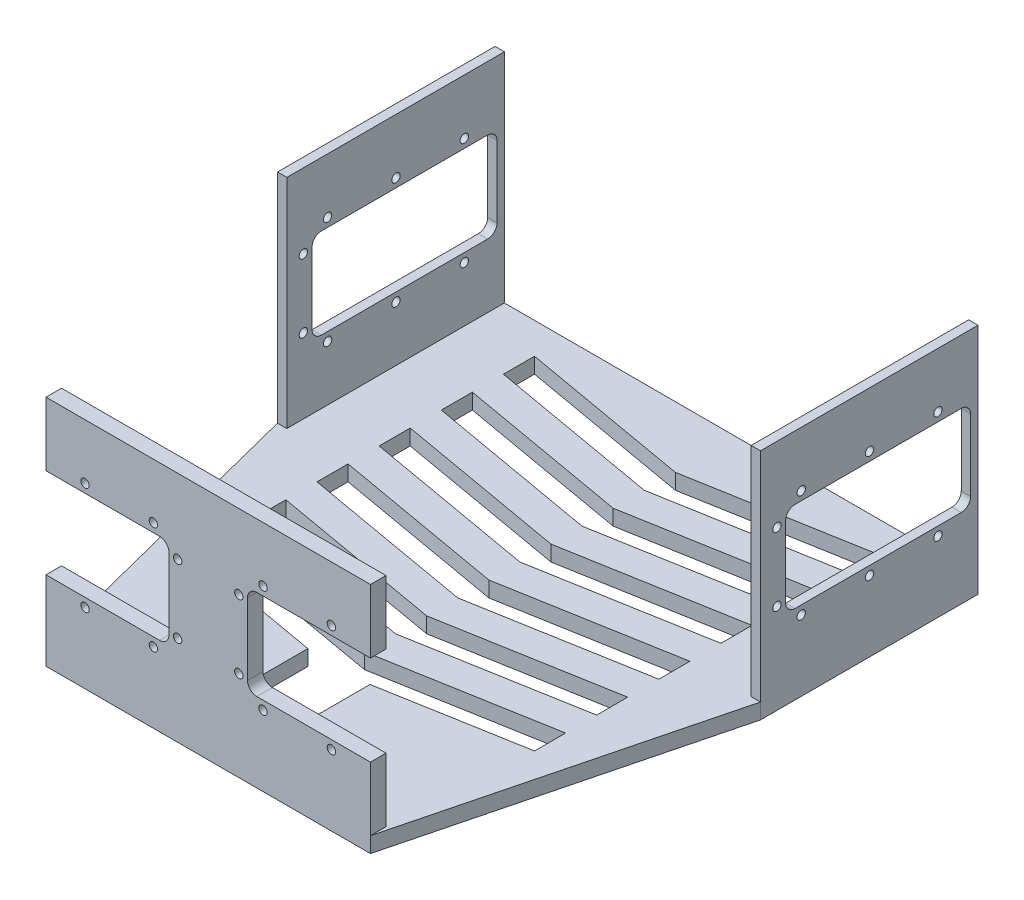
SolidWorks part; units mm, degrees
material "Aluminium 1050"
ref_plane "Front Plane" through (0, 0, 0) normal (0, 0, 1) x (1, 0, 0)
ref_plane "Top Plane" through (0, 0, 0) normal (0, 1, 0) x (1, 0, 0)
ref_plane "Right Plane" through (0, 0, 0) normal (1, 0, 0) x (0, 0, -1)
sketch "Sketch1" plane through (0, 0, 0) normal (0, 1, 0) x (1, 0, 0)
  line L0 (0, 0) -> (104.4, 0)
  line L4 (52.2, 0) -> (52.2, 170) construction
  line L5 (129.9, 100) -> (129.9, 170)
  line L6 (-25.5, 100) -> (-25.5, 170)
  line L7 (-25.5, 170) -> (129.9, 170)
  line L8 (-25.5, 100) -> (129.9, 100) construction
  line L9 (-25.5, 100) -> (0, 0)
  line L10 (104.4, 0) -> (129.9, 100)
  line L12 (-25.5, 0) -> (-25.5, 170) construction
  line L13 (129.9, 0) -> (129.9, 170) construction
  dimension "D1" = 104.4
  dimension "D2" = 170
  dimension "D3" = 77.7
  dimension "D4" = 77.7
  dimension "D5" = 70
extrude "Boss-Extrude1" add sketch "Sketch1" along normal blind 3
sketch "Sketch4" plane through (-25.5, 0, 0) normal (-1, 0, 0) x (0, 0, 1)
  line L0 (-170, 3) -> (-170, 73)
  line L1 (-170, 73) -> (-100, 73)
  line L2 (-100, 73) -> (-100, 3)
  line L3 (-170, 3) -> (-100, 3) construction
  line L4 (-100, 3) -> (-170, 3)
  dimension "D1" = 70
  dimension "D2" = 70
extrude "Boss-Extrude3" add sketch "Sketch4" against normal blind 3
sketch "Sketch5" plane through (129.9, 0, 0) normal (1, 0, 0) x (0, 0, -1)
  line L0 (170, 3) -> (170, 73)
  line L1 (170, 73) -> (100, 73)
  line L2 (100, 73) -> (100, 3)
  line L3 (100, 3) -> (170, 3)
extrude "Boss-Extrude4" add sketch "Sketch5" against normal blind 3
sketch "Sketch7" plane through (0, 0, 0) normal (0, 0, 1) x (1, 0, 0)
  line L7 (0, 3) -> (104.4, 3)
  line L11 (0, 3) -> (0, 73)
  line L15 (104.4, 3) -> (104.4, 73)
  line L29 (0, 0) -> (104.4, 0)
  line L30 (104.4, 0) -> (104.4, 3)
  line L31 (0, 73) -> (104.4, 73)
  point P0 (52.2, -22.1263)
  point P1 (52.2, 47.538)
  point P4 (109.5, -22.1263)
  point P5 (109.5, 47.538)
  point P6 (-5.1, -22.1263)
  point P8 (-5.1, 47.538)
  dimension "D1" = 70
extrude "Boss-Extrude5" add sketch "Sketch7" against normal blind 5
sketch "Sketch8" plane through (-22.5, 0, 0) normal (1, 0, 0) x (0, 0, -1)
  line L0 (111.05, 15.5) -> (164.55, 15.5) construction
  line L1 (167.55, 18.5) -> (167.55, 41.5) construction
  line L2 (164.55, 44.5) -> (111.05, 44.5) construction
  line L3 (108.05, 41.5) -> (108.05, 18.5) construction
  line L4 (135.05, -30.973) -> (135.05, 91.2848) construction
  line L5 (100, 38) -> (170, 38) construction
  line L6 (100, 3) -> (100, 73) construction
  line L7 (170, 73) -> (170, 0) construction
  circle A0 centre (157.05, 47.3) radius 1.35 construction
  circle A1 centre (135.05, 47.3) radius 1.35 construction
  circle A2 centre (113.05, 47.3) radius 1.35 construction
  circle A3 centre (105.25, 41) radius 1.35 construction
  circle A4 centre (105.25, 19) radius 1.35 construction
  circle A5 centre (113.05, 12.7) radius 1.35 construction
  circle A6 centre (157.05, 12.7) radius 1.35 construction
  circle A7 centre (135.05, 12.7) radius 1.35 construction
  arc A8 (164.55, 15.5) -> (167.55, 18.5) centre (164.55, 18.5) ccw construction
  arc A9 (167.55, 41.5) -> (164.55, 44.5) centre (164.55, 41.5) ccw construction
  arc A10 (111.05, 44.5) -> (108.05, 41.5) centre (111.05, 41.5) ccw construction
  arc A11 (111.05, 15.5) -> (108.05, 18.5) centre (111.05, 18.5) cw construction
  dimension "D1" = 2.7
  dimension "D2" = 2.7
  dimension "D3" = 2.7
  dimension "D4" = 2.7
  dimension "D5" = 2.7
  dimension "D6" = 2.7
  dimension "D7" = 2.7
  dimension "D8" = 2.7
sketch "Sketch22" plane through (0, 0, 0) normal (0, -1, 0) x (1, 0, 0)
  line L0 (129.9, -170) -> (-25.5, -170)
  line L1 (-25.5, -170) -> (-25.5, -100)
  line L2 (-25.5, -100) -> (0, 0)
  line L3 (0, 0) -> (104.4, 0)
  line L4 (104.4, 0) -> (129.9, -100)
  line L5 (129.9, -100) -> (129.9, -170)
extrude "Boss-Extrude13" add sketch "Sketch22" along normal blind 2
sketch "Sketch26" plane through (-25.5, 0, 0) normal (-1, 0, 0) x (0, 0, 1)
  line L0 (-170, 38) -> (-100, 38)
  line L1 (-170, 23.5) -> (-100, 23.5)
  line L2 (-170, 52.5) -> (-100, 52.5)
  circle A0 centre (-157.1137, 55.3) radius 1.35
  circle A1 centre (-135.1137, 55.3) radius 1.35
  circle A2 centre (-113.1137, 55.3) radius 1.35
  circle A3 centre (-105.3137, 49) radius 1.35
  circle A4 centre (-105.3137, 27) radius 1.35
  circle A5 centre (-113.1137, 20.7) radius 1.35
  circle A6 centre (-157.1137, 20.7) radius 1.35
  circle A7 centre (-135.1137, 20.7) radius 1.35
  dimension "D1" = 2.7
  dimension "D2" = 2.7
  dimension "D3" = 2.7
  dimension "D4" = 2.7
  dimension "D5" = 2.7
  dimension "D6" = 2.7
  dimension "D7" = 2.7
  dimension "D8" = 2.7
  dimension "D9" = 14.5
  dimension "D10" = 14.5
extrude "Cut-Extrude1" cut sketch "Sketch26" against normal through all both and the other way through all contours A6 | A5 | A4 | A3 | A2 | A1 | A0 | A7
sketch "Sketch28" plane through (-22.5, 0, 0) normal (1, 0, 0) x (0, 0, -1)
  line L2 (167.6137, 49.5) -> (167.6137, 26.5)
  line L3 (164.6137, 23.5) -> (111.1137, 23.5)
  line L4 (108.1137, 26.5) -> (108.1137, 49.5)
  line L5 (111.1137, 52.5) -> (164.6137, 52.5)
  arc A0 (167.6137, 26.5) -> (164.6137, 23.5) centre (164.6137, 26.5) cw
  arc A1 (111.1137, 23.5) -> (108.1137, 26.5) centre (111.1137, 26.5) cw
  arc A2 (108.1137, 49.5) -> (111.1137, 52.5) centre (111.1137, 49.5) cw
  arc A3 (111.1137, 52.5) -> (108.1137, 49.5) centre (111.1137, 49.5) ccw construction
  arc A4 (164.6137, 52.5) -> (167.6137, 49.5) centre (164.6137, 49.5) cw
extrude "Cut-Extrude3" cut sketch "Sketch28" against normal through all both and the other way through all
sketch "Sketch29" plane through (0, 0, -5) normal (0, 0, -1) x (-1, 0, 0)
  line L0 (-52.2, 3) -> (-52.2, 73)
  line L1 (-104.4, 3) -> (0, 3) construction
  line L2 (0, 73) -> (-104.4, 73) construction
  line L3 (5.1, 38) -> (-109.5, 38)
  line L6 (5.1, 3) -> (5.1, 73)
  line L7 (-109.5, 3) -> (-109.5, 73)
  dimension "D1" = 57.3
  dimension "D2" = 57.3
sketch "Sketch31" plane through (0, 0, -5) normal (0, 0, -1) x (-1, 0, 0)
  line L0 (-36.5639, 52.5) -> (0, 52.5)
  line L1 (-36.5639, 52.5) -> (16.9361, 52.5) construction
  line L2 (0, 3) -> (0, 73) construction
  line L3 (0, 52.5) -> (0, 23.5)
  line L4 (16.9361, 23.5) -> (-36.5639, 23.5) construction
  line L5 (0, 23.5) -> (-36.5639, 23.5)
  line L6 (-39.5639, 26.5) -> (-39.5639, 49.5)
  line L7 (-52.2, 3) -> (-52.2, 73)
  line L8 (-64.8361, 26.5) -> (-64.8361, 49.5)
  line L9 (-104.4, 23.5) -> (-67.8361, 23.5)
  line L10 (-104.4, 52.5) -> (-104.4, 23.5)
  line L11 (-67.8361, 52.5) -> (-104.4, 52.5)
  arc A0 (-36.5639, 52.5) -> (-39.5639, 49.5) centre (-36.5639, 49.5) ccw construction
  arc A1 (-36.5639, 23.5) -> (-39.5639, 26.5) centre (-36.5639, 26.5) cw
  arc A2 (-36.5639, 52.5) -> (-39.5639, 49.5) centre (-36.5639, 49.5) ccw
  circle A3 centre (-12.5639, 55.3) radius 1.35
  circle A4 centre (-34.5639, 55.3) radius 1.35
  circle A5 centre (-42.3639, 49) radius 1.35
  circle A6 centre (-42.3639, 27) radius 1.35
  circle A7 centre (-34.5639, 20.7) radius 1.35
  circle A8 centre (-12.5639, 20.7) radius 1.35
  arc A9 (0, 50.9015) -> (0, 25.0985) centre (5.4361, 38) ccw
  arc A10 (-104.4, 50.9015) -> (-104.4, 25.0985) centre (-109.8361, 38) cw
  circle A11 centre (-91.8361, 20.7) radius 1.35
  circle A12 centre (-69.8361, 20.7) radius 1.35
  circle A13 centre (-62.0361, 27) radius 1.35
  circle A14 centre (-62.0361, 49) radius 1.35
  circle A15 centre (-69.8361, 55.3) radius 1.35
  circle A16 centre (-91.8361, 55.3) radius 1.35
  arc A17 (-67.8361, 52.5) -> (-64.8361, 49.5) centre (-67.8361, 49.5) cw
  arc A18 (-67.8361, 23.5) -> (-64.8361, 26.5) centre (-67.8361, 26.5) ccw
  line M2 (-104.4, 73) -> (-104.4, 3)
  line M4 (0, 3) -> (0, 73)
  dimension "D1" = 28
extrude "Cut-Extrude4" cut sketch "Sketch31" against normal through all both and the other way through all contours A9 L0 A2 L6 A1 L5 M4 | L3 A9 | L9 A18 L8 A17 L11 A10 M2 | A10 L10 | A11 | A12 | A13 | A14 | A15 | A16 | A4 | A5 | A6 | A7 | A8 | A3
sketch "Sketch32" plane through (0, -2, 0) normal (0, -1, 0) x (-1, 0, 0)
  line L0 (-52.2, 150.302) -> (-52.2, 20.302)
  line L1 (-62.2, 152.0653) -> (-62.2, 22.0653)
  line L2 (-42.2, 152.0653) -> (-42.2, 22.0653)
  line L5 (-107.2, 160) -> (-107.2, 30)
  line L6 (2.8, 160) -> (2.8, 30)
  line L9 (-52.2, 150.302) -> (2.8, 160)
  line L10 (-107.2, 160) -> (-52.2, 150.302)
  line L11 (-52.2, 140.302) -> (2.8, 150)
  line L12 (-107.2, 150) -> (-52.2, 140.302)
  line L13 (-52.2, 130.302) -> (2.8, 140)
  line L14 (-107.2, 140) -> (-52.2, 130.302)
  line L15 (-52.2, 120.302) -> (2.8, 130)
  line L16 (-107.2, 130) -> (-52.2, 120.302)
  line L17 (-52.2, 110.302) -> (2.8, 120)
  line L18 (-107.2, 120) -> (-52.2, 110.302)
  line L19 (-52.2, 100.302) -> (2.8, 110)
  line L20 (-107.2, 110) -> (-52.2, 100.302)
  line L21 (-52.2, 90.302) -> (2.8, 100)
  line L22 (-107.2, 100) -> (-52.2, 90.302)
  line L23 (-52.2, 80.302) -> (2.8, 90)
  line L24 (-107.2, 90) -> (-52.2, 80.302)
  line L25 (-52.2, 70.302) -> (2.8, 80)
  line L26 (-107.2, 80) -> (-52.2, 70.302)
  line L27 (-52.2, 60.302) -> (2.8, 70)
  line L28 (-107.2, 70) -> (-52.2, 60.302)
  line L29 (-52.2, 50.302) -> (2.8, 60)
  line L30 (-107.2, 60) -> (-52.2, 50.302)
  line L31 (-52.2, 40.302) -> (2.8, 50)
  line L32 (-107.2, 50) -> (-52.2, 40.302)
  line L33 (-52.2, 30.302) -> (2.8, 40)
  line L34 (-107.2, 40) -> (-52.2, 30.302)
  line L35 (-52.2, 20.302) -> (2.8, 30)
  line L36 (-107.2, 30) -> (-52.2, 20.302)
  line L37 (-107.2, 170) -> (-107.2, 0) construction
  line L38 (-62.2, 170) -> (-62.2, 0) construction
  line L39 (-52.2, 170) -> (-52.2, 0) construction
  line L40 (-42.2, 170) -> (-42.2, 0) construction
  line L41 (2.8, 170) -> (2.8, 0) construction
  dimension "D1" = 10
  dimension "D2" = 10
  dimension "D3" = 55
  dimension "D4" = 55
extrude "Cut-Extrude6" cut sketch "Sketch32" against normal up to next (5 mm away) contours L5 L12 L1 L10 | L1 L12 L0 L10 | L0 L11 L2 L9 | L2 L11 L6 L9 | L5 L16 L1 L14 | L1 L16 L0 L14 | L0 L15 L2 L13 | L2 L15 L6 L13 | L5 L20 L1 L18 | L1 L20 L0 L18 | L0 L19 L2 L17 | L2 L19 L6 L17 | L5 L24 L1 L22 | L1 L24 L0 L22 | L0 L23 L2 L21 | L2 L23 L6 L21 | L5 L28 L1 L26 | L1 L28 L0 L26 | L0 L27 L2 L25 | L2 L27 L6 L25 | L5 L32 L1 L30 | L1 L32 L0 L30 | L0 L31 L2 L29 | L2 L31 L6 L29 | L1 L34 L0 L32 | L0 L33 L2 L31 | L0 L35 L2 L33 | L1 L36 L0 L34
